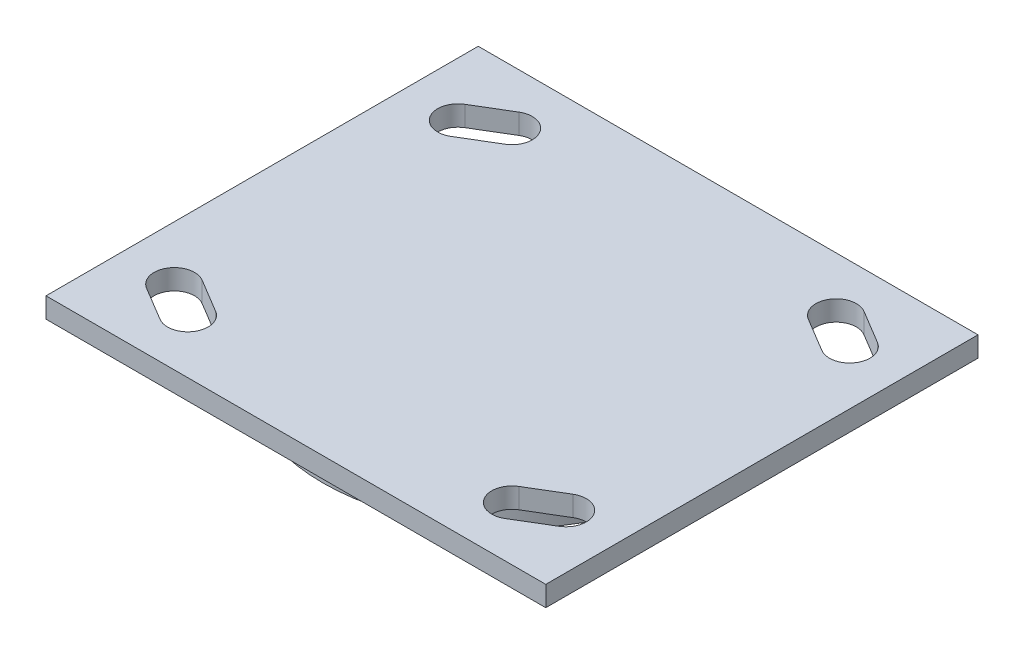
SolidWorks part; units mm, degrees
ref_plane "Front Plane" through (0, 0, 0) normal (0, 0, 1) x (1, 0, 0)
ref_plane "Top Plane" through (0, 0, 0) normal (0, 1, 0) x (1, 0, 0)
ref_plane "Right Plane" through (0, 0, 0) normal (1, 0, 0) x (0, 0, -1)
sketch "Sketch1" plane through (0, 0, 0) normal (0, 0, 1) x (1, 0, 0)
  line L1 (-58.7375, 0) -> (58.7375, 0)
  line L2 (-58.7375, 0) -> (-58.7375, -4.7625)
  line L3 (-58.7375, -4.7625) -> (58.7375, -4.7625)
  line L4 (58.7375, 0) -> (58.7375, -4.7625)
  dimension "Plate Length" = 117.475
  dimension "Plate Thickness" = 4.7625
extrude "Boss-Extrude1" add sketch "Sketch1" along normal mid plane 101.6
sketch "Sketch2" plane through (0, 0, 0) normal (0, 1, 0) x (1, 0, 0)
  line L0 (-38.1, 38.1) -> (-46.0375, 33.3375) construction
  line L1 (-35.6497, 34.0162) -> (-43.5872, 29.2537)
  line L2 (-40.5503, 42.1838) -> (-48.4878, 37.4213)
  line L3 (0, 0) -> (0, 50.8) construction
  line L4 (0, 0) -> (58.7375, 0) construction
  line L5 (58.7375, -50.8) -> (58.7375, 50.8) construction
  line L6 (58.7375, 50.8) -> (-58.7375, 50.8) construction
  line L7 (-38.1, -38.1) -> (-46.0375, -33.3375) construction
  line L8 (-35.6497, -34.0162) -> (-43.5872, -29.2537)
  line L9 (-40.5503, -42.1838) -> (-48.4878, -37.4213)
  line L10 (38.1, 38.1) -> (46.0375, 33.3375) construction
  line L11 (35.6497, 34.0162) -> (43.5872, 29.2537)
  line L12 (40.5503, 42.1838) -> (48.4878, 37.4213)
  line L13 (38.1, -38.1) -> (46.0375, -33.3375) construction
  line L14 (35.6497, -34.0162) -> (43.5872, -29.2537)
  line L15 (40.5503, -42.1838) -> (48.4878, -37.4213)
  arc A0 (-35.6497, 34.0162) -> (-40.5503, 42.1838) centre (-38.1, 38.1) ccw
  arc A1 (-48.4878, 37.4213) -> (-43.5872, 29.2537) centre (-46.0375, 33.3375) ccw
  arc A2 (-35.6497, -34.0162) -> (-40.5503, -42.1838) centre (-38.1, -38.1) cw
  arc A3 (-48.4878, -37.4213) -> (-43.5872, -29.2537) centre (-46.0375, -33.3375) cw
  arc A4 (35.6497, 34.0162) -> (40.5503, 42.1838) centre (38.1, 38.1) cw
  arc A5 (48.4878, 37.4213) -> (43.5872, 29.2537) centre (46.0375, 33.3375) cw
  arc A6 (35.6497, -34.0162) -> (40.5503, -42.1838) centre (38.1, -38.1) ccw
  arc A7 (48.4878, -37.4213) -> (43.5872, -29.2537) centre (46.0375, -33.3375) ccw
  point P2 (-42.0687, 35.7188)
  point P17 (-42.0687, -35.7188)
  point P24 (42.0688, 35.7188)
  point P31 (42.0687, -35.7187)
  dimension "D3" = 92.075
  dimension "D5" = 76.2
  dimension "D1" = 9.525
  dimension "D2" = 76.2
  dimension "D4" = 66.675
extrude "1-2 holes" cut sketch "Sketch2" against normal through all
sketch "Sketch3" plane through (0, 0, 0) normal (0, 1, 0) x (1, 0, 0)
  line L0 (0, 0) -> (0, 50.8) construction
  line L1 (58.7375, 50.8) -> (-58.7375, 50.8) construction
  line L2 (0, 0) -> (58.7375, 0) construction
  line L3 (58.7375, -50.8) -> (58.7375, 50.8) construction
  circle A0 centre (-57.15, 52.3875) radius 4.7625
  circle A1 centre (57.15, 52.3875) radius 4.7625
  circle A2 centre (57.15, -52.3875) radius 4.7625
  circle A3 centre (-57.15, -52.3875) radius 4.7625
  dimension "D1" = 9.525
  dimension "D2" = 114.3
  dimension "D3" = 104.775
extrude "3-holes" [suppressed] cut sketch "Sketch3" against normal through all
sketch "Sketch4" plane through (0, 0, 0) normal (0, 0, 1) x (1, 0, 0)
  line L0 (0, -4.7625) -> (0, -25.5651) construction
  line L1 (0, -25.5651) -> (43.18, -25.5651)
  line L2 (43.18, -25.5651) -> (43.18, -14.4526)
  line L3 (43.18, -14.4526) -> (40.64, -14.4526)
  line L4 (40.64, -14.4526) -> (40.64, -11.9126)
  line L5 (40.64, -11.9126) -> (44.45, -11.9126)
  line L6 (44.45, -11.9126) -> (44.45, -4.7625)
  line L7 (44.45, -4.7625) -> (0, -4.7625)
  line L8 (-58.7375, -4.7625) -> (58.7375, -4.7625) construction
  line L9 (0, -4.7625) -> (0, -25.5651)
  line L10 (-84.1558, -99.5184) -> (-31.2338, -25.5651) construction
  line L11 (-42.8442, -129.0816) -> (31.2338, -25.5651) construction
  line L12 (-63.5, -114.3) -> (0, -25.5651) construction
  line L13 (0, 0) -> (0, -190.5) construction
  line L14 (58.7375, 0) -> (-58.7375, 0) construction
  circle A0 centre (-63.5, -114.3) radius 76.2 construction
  arc A1 (-84.1558, -99.5184) -> (-42.8442, -129.0816) centre (-63.5, -114.3) ccw construction
  point P13 (-63.5, -38.1)
  point P14 (-63.5, -190.5)
  dimension "Wheel Dia" = 152.4
  dimension "D7" = 50.8
  dimension "Mount Height" = 190.5
  dimension "Offset" = 63.5
  dimension "D1" = 7.1501
  dimension "D2" = 11.1125
  dimension "D3" = 2.54
  dimension "D4" = 88.9
  dimension "D5" = 86.36
  dimension "D6" = 81.28
revolve "Revolve1" add sketch "Sketch4" angle 360 about L0
ref_plane "Plane1" through (-63.5, 0, 0) normal (1, 0, 0) x (0, 0, -1)
sketch "Sketch5" plane through (-63.5, 0, 0) normal (1, 0, 0) x (0, 0, -1)
  line L1 (-25.4, -38.1) -> (25.4, -38.1)
  line L2 (-25.4, -38.1) -> (-25.4, -190.5)
  line L3 (-25.4, -190.5) -> (25.4, -190.5)
  line L4 (25.4, -38.1) -> (25.4, -190.5)
  dimension "Wheel Width" = 50.8
sketch "Sketch6" plane through (-63.5, 0, 0) normal (1, 0, 0) x (0, 0, -1)
  line L0 (-25.4, -68.58) -> (-25.4, -47.3364)
  line L1 (-16.1636, -38.1) -> (-14.1432, -38.1)
  line L2 (25.4, -47.3364) -> (25.4, -68.58)
  line L3 (-25.4, -38.1) -> (25.4, -38.1) construction
  line L4 (-25.4, -38.1) -> (-25.4, -190.5) construction
  line L5 (25.4, -38.1) -> (25.4, -190.5) construction
  line L6 (-111.1453, -114.3) -> (111.1453, -114.3) construction
  line L7 (-25.4, -68.58) -> (-26.67, -68.58)
  line L8 (-26.67, -68.58) -> (-26.67, -71.12)
  line L9 (-26.67, -93.6625) -> (-29.845, -93.6625)
  line L10 (-29.845, -93.6625) -> (-29.845, -114.3)
  line L11 (0, -38.1) -> (0, -256.5466) construction
  line L12 (0, -38.1) -> (0, -190.5) construction
  line L13 (29.845, -93.6625) -> (29.845, -114.3)
  line L14 (26.67, -93.6625) -> (29.845, -93.6625)
  line L17 (-29.845, -114.3) -> (29.845, -114.3)
  line L18 (-14.1432, -38.1) -> (-14.1432, -40.4812)
  line L19 (-14.1432, -40.4812) -> (-10.1023, -40.4812)
  line L20 (-10.1023, -40.4812) -> (-10.1023, -38.1)
  line L21 (-6.0614, -38.1) -> (-6.0614, -40.4812)
  line L22 (-6.0614, -40.4812) -> (-2.0205, -40.4812)
  line L23 (-2.0205, -40.4812) -> (-2.0205, -38.1)
  line L24 (2.0205, -40.4812) -> (2.0205, -38.1)
  line L25 (6.0614, -40.4812) -> (2.0205, -40.4812)
  line L26 (6.0614, -38.1) -> (6.0614, -40.4812)
  line L27 (10.1023, -40.4812) -> (10.1023, -38.1)
  line L28 (14.1432, -40.4812) -> (10.1023, -40.4812)
  line L29 (14.1432, -38.1) -> (14.1432, -40.4812)
  line L30 (-10.1023, -38.1) -> (-6.0614, -38.1)
  line L31 (-2.0205, -38.1) -> (2.0205, -38.1)
  line L32 (6.0614, -38.1) -> (10.1023, -38.1)
  line L33 (14.1432, -38.1) -> (16.1636, -38.1)
  line L34 (-26.67, -71.12) -> (-23.495, -71.12)
  line L35 (-11.3484, -83.7958) -> (-5.4383, -84.3129)
  line L36 (-2.54, -87.4758) -> (-2.54, -93.6625)
  line L37 (-17.145, -77.47) -> (-17.145, -208.9815) construction
  line L38 (-26.67, -93.6625) -> (-2.54, -93.6625)
  line L39 (26.67, -93.6625) -> (2.54, -93.6625)
  line L40 (2.54, -87.4758) -> (2.54, -93.6625)
  line L41 (11.3484, -83.7958) -> (5.4383, -84.3129)
  line L42 (26.67, -71.12) -> (23.495, -71.12)
  line L43 (26.67, -68.58) -> (26.67, -71.12)
  line L44 (25.4, -68.58) -> (26.67, -68.58)
  arc A0 (-25.4, -47.3364) -> (-16.1636, -38.1) centre (-16.1636, -47.3364) cw
  arc A1 (16.1636, -38.1) -> (25.4, -47.3364) centre (16.1636, -47.3364) cw
  arc A2 (-23.495, -71.12) -> (-17.145, -77.47) centre (-23.495, -77.47) cw
  arc A3 (-17.145, -77.47) -> (-11.3484, -83.7958) centre (-10.795, -77.47) ccw
  arc A4 (-5.4383, -84.3129) -> (-2.54, -87.4758) centre (-5.715, -87.4758) cw
  arc A5 (5.4383, -84.3129) -> (2.54, -87.4758) centre (5.715, -87.4758) ccw
  arc A6 (17.145, -77.47) -> (11.3484, -83.7958) centre (10.795, -77.47) cw
  arc A7 (23.495, -71.12) -> (17.145, -77.47) centre (23.495, -77.47) ccw
  dimension "D1" = 9.2364
  dimension "D13" = 6.35
  dimension "D16" = 3.175
  dimension "D2" = 1.27
  dimension "D3" = 3.175
  dimension "D4" = 41.275
  dimension "D5" = 91.44
  dimension "D6" = 32.3273
  dimension "D7" = 4.0409
  dimension "D8" = 2.3813
  dimension "D9" = 4.0409
  dimension "D10" = 2.0205
  dimension "D11" = 3.175
  dimension "D12" = 2.54
  dimension "D14" = 5
  dimension "D15" = 2.54
revolve "Revolve2" add sketch "Sketch6" angle 360 about L6
sketch "Sketch7" plane through (0, -25.5651, 0) normal (0, -1, 0) x (1, 0, 0)
  line L0 (-42.8625, 29.845) -> (-84.1375, 29.845) construction
  line L1 (-139.7, 35.1536) -> (31.2338, 35.1536)
  line L2 (-139.7, 35.1536) -> (-139.7, -35.1536)
  line L3 (-139.7, -35.1536) -> (31.2338, -35.1536)
  line L4 (31.2338, 35.1536) -> (31.2338, -35.1536)
  line L6 (-139.7, 10.1023) -> (-139.7, 6.0614) construction
  line L8 (31.2338, -35.1536) -> (31.2338, 35.1536) construction
  line L9 (-31.2338, 35.1536) -> (-31.2338, -35.1536) construction
  line L14 (-31.2338, 29.8155) -> (31.2338, 29.8155) construction
  line L15 (-31.2338, 29.8155) -> (-31.2338, 27.0469) construction
  line L16 (-31.2338, 27.0469) -> (31.2338, 27.0469) construction
  line L17 (31.2338, 29.8155) -> (31.2338, 27.0469) construction
  line L18 (-31.2338, -27.0469) -> (31.2338, -27.0469) construction
  line L19 (-31.2338, -27.0469) -> (-31.2338, -29.8155) construction
  line L20 (-31.2338, -29.8155) -> (31.2338, -29.8155) construction
  line L21 (31.2338, -27.0469) -> (31.2338, -29.8155) construction
  circle A0 centre (0, 0) radius 43.18 construction
  circle A1 centre (0, 0) radius 43.18 construction
  dimension "D1" = 5.3086
  dimension "D3" = 2.7686
extrude "Boss-Extrude2" add sketch "Sketch7" along normal up to vertex (164.9349 mm away) separate body up to point (-63.5, -190.5, -25.4)
sketch "Sketch8" plane through (0, 0, 35.1536) normal (0, 0, 1) x (1, 0, 0)
  line L0 (-84.1558, -99.5184) -> (-31.2338, -25.5651) construction
  line L1 (-42.8442, -129.0816) -> (31.2338, -25.5651) construction
  line L2 (-84.1558, -99.5184) -> (-31.2338, -25.5651)
  line L3 (-42.8442, -129.0816) -> (31.2338, -25.5651)
  arc A0 (-84.1558, -99.5184) -> (-42.8442, -129.0816) centre (-63.5, -114.3) ccw construction
  arc A1 (-84.1558, -99.5184) -> (-42.8442, -129.0816) centre (-63.5, -114.3) ccw
extrude "Cut-Extrude1" cut sketch "Sketch8" against normal through all and the other way through all flip side to cut
sketch "Sketch9" plane through (0, -144.3067, 0) normal (-1, 0, 0) x (0, 0, -1)
  line L0 (35.1536, 46.1933) -> (35.1536, -106.2067)
  line L2 (35.1536, -118.7416) -> (-35.1536, -118.7416) construction
  line L3 (27.0469, -118.7416) -> (32.385, -106.2067)
  line L4 (27.0469, -118.7416) -> (29.8155, -118.7416) construction
  line L5 (32.385, -106.2067) -> (32.385, 46.1933)
  line L6 (35.1536, 46.1933) -> (32.385, 46.1933)
  line L7 (35.1536, -118.7416) -> (35.1536, -15.2251) construction
  line L8 (-25.4, 46.1933) -> (25.4, 46.1933) construction
  line L9 (35.1536, -106.2067) -> (29.8155, -118.7416)
  line L10 (27.0469, -118.7416) -> (29.8155, -118.7416)
  line L11 (0, -144.3067) -> (0, 46.1933) construction
  line L12 (-27.0469, -118.7416) -> (-29.8155, -118.7416)
  line L13 (-35.1536, -106.2067) -> (-29.8155, -118.7416)
  line L14 (-35.1536, 46.1933) -> (-32.385, 46.1933)
  line L15 (-32.385, -106.2067) -> (-32.385, 46.1933)
  line L16 (-27.0469, -118.7416) -> (-32.385, -106.2067)
  line L17 (-35.1536, 46.1933) -> (-35.1536, -106.2067)
  dimension "D1" = 2.7686
  dimension "D2" = 2.7686
extrude "Cut-Extrude3" cut sketch "Sketch9" against normal through all and the other way through all flip side to cut
sketch "Sketch10" plane through (0, 0, 35.1536) normal (0, 0, 1) x (1, 0, 0)
  line L1 (-63.5, -101.4684) -> (-74.6125, -107.8842)
  line L2 (-74.6125, -107.8842) -> (-74.6125, -120.7158)
  line L3 (-74.6125, -120.7158) -> (-63.5, -127.1316)
  line L4 (-63.5, -127.1316) -> (-52.3875, -120.7158)
  line L5 (-52.3875, -120.7158) -> (-52.3875, -107.8842)
  line L6 (-52.3875, -107.8842) -> (-63.5, -101.4684)
  circle A0 centre (-63.5, -114.3) radius 11.1125 construction
  dimension "D1" = 22.225
extrude "Boss-Extrude3" add sketch "Sketch10" along normal blind 7.9375 separate body
sketch "Sketch11" plane through (0, 0, 43.0911) normal (0, 0, 1) x (1, 0, 0)
  circle A0 centre (-63.5, -114.3) radius 11.1125 construction
  circle A1 centre (-63.5, -114.3) radius 11.1125
extrude "Cut-Extrude4" cut sketch "Sketch11" against normal through all draft 60 flip side to cut
mirror "Mirror1" about plane through (0, 0, 0) normal (0, 0, 1) of bodies 113
sketch "Sketch12" plane through (0, 0, -32.385) normal (0, 0, 1) x (1, 0, 0)
  circle A0 centre (-63.5, -114.3) radius 10.795
  dimension "D1" = 21.59
extrude "Boss-Extrude4" add sketch "Sketch12" along normal up to surface (64.77 mm away)
combine bodies "Combine1" operation type add bodies to combine 115 114 113 104 102
ref_plane "Ground" through (0, -190.5, 0) normal (0, 1, 0) x (1, 0, 0)
sketch "Sketch13" plane through (0, -11.9126, 0) normal (0, -1, 0) x (1, 0, 0)
  circle A0 centre (0, 0) radius 298.45
  circle A1 centre (0, 0) radius 44.45 construction
  dimension "D1" = 254
extrude "Cut-Extrude5" cut sketch "Sketch13" along normal blind 254
equation "\"D5@Sketch6\" = \"Wheel Dia@Sketch4\"*.6"
equation "\"D1@Sketch6\" = \"Wheel Width@Sketch5\"/5.5"
equation "\"D7@Sketch6\" = \"D6@Sketch6\"/8"
equation "\"D9@Sketch6\" = \"D7@Sketch6\""
equation "\"D10@Sketch6\" = \"D7@Sketch6\"/2"
